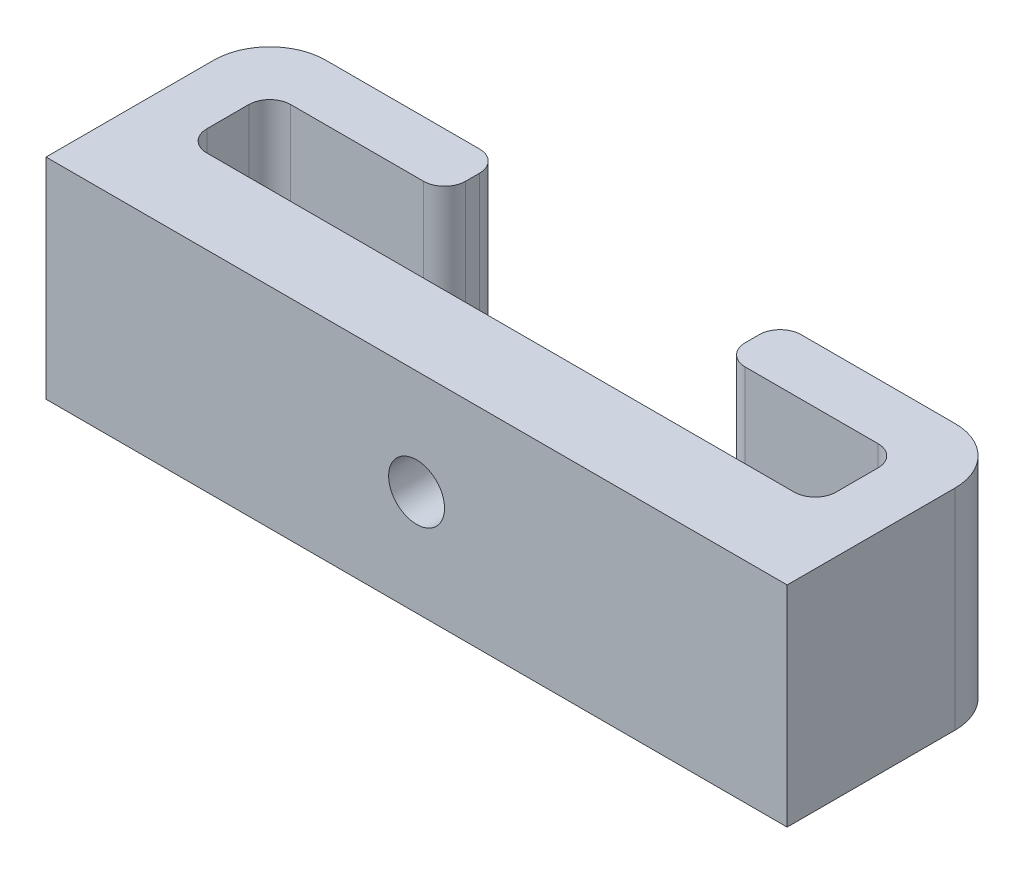
SolidWorks part; units mm, degrees
material "ABS"
ref_plane "Plan de face" through (0, 0, 0) normal (0, 0, 1) x (1, 0, 0)
ref_plane "Plan de dessus" through (0, 0, 0) normal (0, 1, 0) x (1, 0, 0)
ref_plane "Plan de droite" through (0, 0, 0) normal (1, 0, 0) x (0, 0, -1)
sketch "Esquisse1" plane through (0, 0, 0) normal (0, 1, 0) x (1, 0, 0)
  line L0 (-10, 6) -> (-22.5, 6)
  line L1 (-22.5, 6) -> (-22.5, 0)
  line L2 (-22.5, 0) -> (22.5, 0)
  line L3 (0, 0) -> (0, 6) construction
  line L4 (22.5, 6) -> (22.5, 0)
  line L5 (10, 6) -> (22.5, 6)
  dimension "D1" = 45
  dimension "D2" = 20
  dimension "D3" = 6
extrude "Extru.-Mince1" add sketch "Esquisse1" along normal mid plane 15 thin
sketch "Esquisse4" plane through (0, 0, 4) normal (0, 0, 1) x (1, 0, 0)
  line L4 (-26.5, -7.5) -> (26.5, -7.5)
  line L5 (26.5, -7.5) -> (26.5, 7.5)
  line L6 (26.5, 7.5) -> (-26.5, 7.5)
  line L7 (-26.5, 7.5) -> (-26.5, -7.5)
  line L8 (-26.5, -7.5) -> (26.5, -7.5)
  line L9 (26.5, -7.5) -> (26.5, 7.5)
  line L10 (26.5, 7.5) -> (-26.5, 7.5)
  line L11 (-26.5, 7.5) -> (-26.5, -7.5)
  dimension "D1" = 0
extrude "Boss.-Extru.1" add sketch "Esquisse4" along normal blind 2
hole_wizard "Fraisage pour vis à tête fraisée M41" positions "Esquisse3" profile "Esquisse2" countersink size "M4" standard "Ansi Metric" end condition through all
sketch "Esquisse3" plane through (0, 0, 0) normal (0, 0, -1) x (-1, 0, 0)
  point P0 (0, 0)
sketch "Esquisse2" plane through (0, 0, 0) normal (1, 0, 0) x (0, 1, 0)
  line L0 (0, 0) -> (0, 6)
  line L1 (0, 6) -> (2, 6)
  line L2 (2, 6) -> (2, 2)
  line L3 (2, 2) -> (4, 0)
  line L5 (4, 0) -> (0, 0)
  line L6 (-2, 2) -> (-4, 0) construction
  line L11 (0, -6.35) -> (0, 107.95) construction
  dimension "Diamètre du perçage jusqu'au prochain" = 4
  dimension "Profondeur du perçage jusqu'au prochain" = 6
  dimension "Diamètre du fraisage entrant" = 8
  dimension "Angle du fraisage entrant" = 90
fillet "Congé1" radius 1.5 8 edges at (10, 0, -10) (22.5, 0, -6) (22.5, 0, 0) (10, 0, -6) (-10, 0, -10) (-10, 0, -6) (-22.5, 0, -6) (-22.5, 0, 0)
fillet "Congé2" radius 4 2 edges at (-26.5, 0, -10) (26.5, 0, -10)
